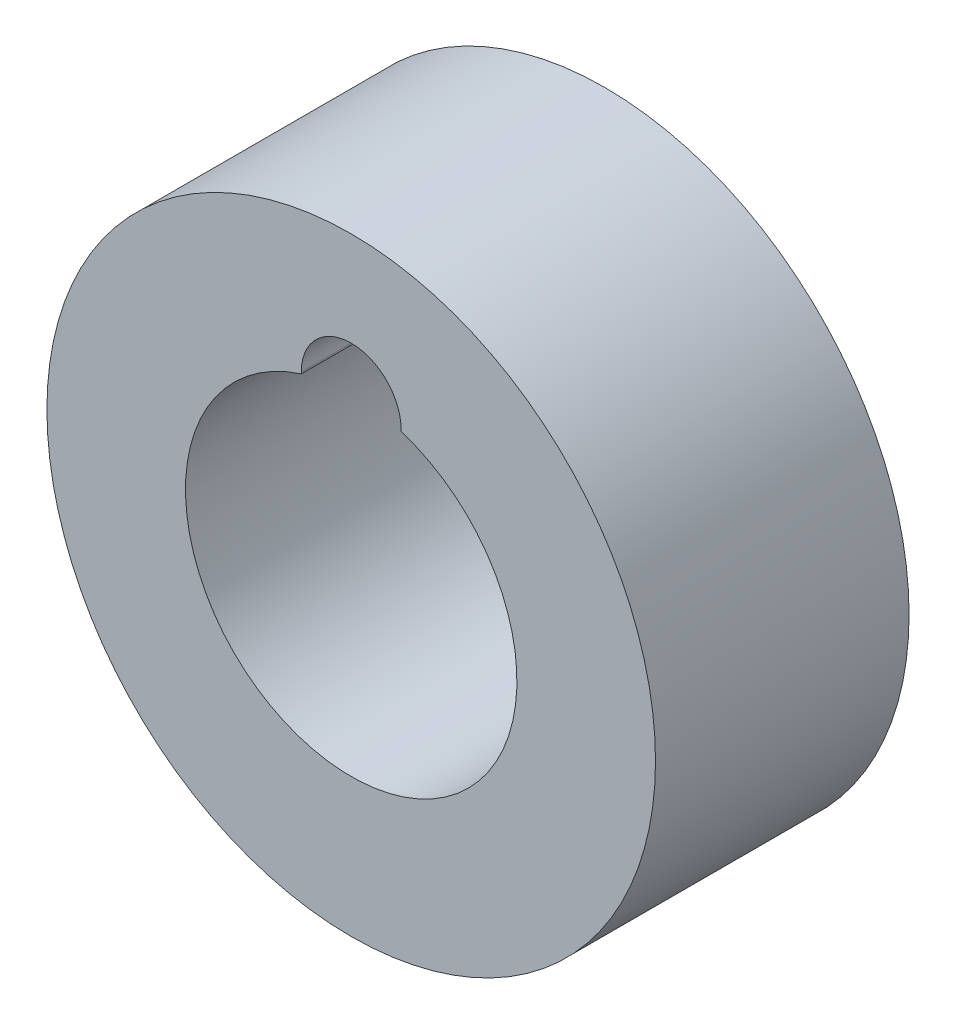
SolidWorks part; units mm, degrees
ref_plane "Alzado" through (0, 0, 0) normal (0, 0, 1) x (1, 0, 0)
ref_plane "Planta" through (0, 0, 0) normal (0, 1, 0) x (1, 0, 0)
ref_plane "Vista lateral" through (0, 0, 0) normal (1, 0, 0) x (0, 0, -1)
sketch "Croquis1" plane through (0, 0, 0) normal (0, 0, 1) x (1, 0, 0)
  circle A0 centre (0, 0) radius 4.15
  circle A1 centre (0, 0) radius 7.62
  dimension "D1" = 8.3
  dimension "D2" = 15.24
extrude "Saliente-Extruir1" add sketch "Croquis1" along normal blind 6.35
sketch "Croquis2" plane through (0, 0, 6.35) normal (0, 0, 1) x (1, 0, 0)
  line L0 (0, 0) -> (0, 4) construction
  line L1 (-1.25, 0) -> (-1.25, 4)
  line L2 (1.25, 0) -> (1.25, 4)
  circle A0 centre (0, 0) radius 4 construction
  arc A1 (-1.25, 0) -> (1.25, 0) centre (0, 0) ccw
  arc A2 (1.25, 4) -> (-1.25, 4) centre (0, 4) ccw
  point P4 (0, 2)
  dimension "D1" = 8
  dimension "D2" = 1.25
extrude "Cortar-Extruir1" cut sketch "Croquis2" against normal through all
